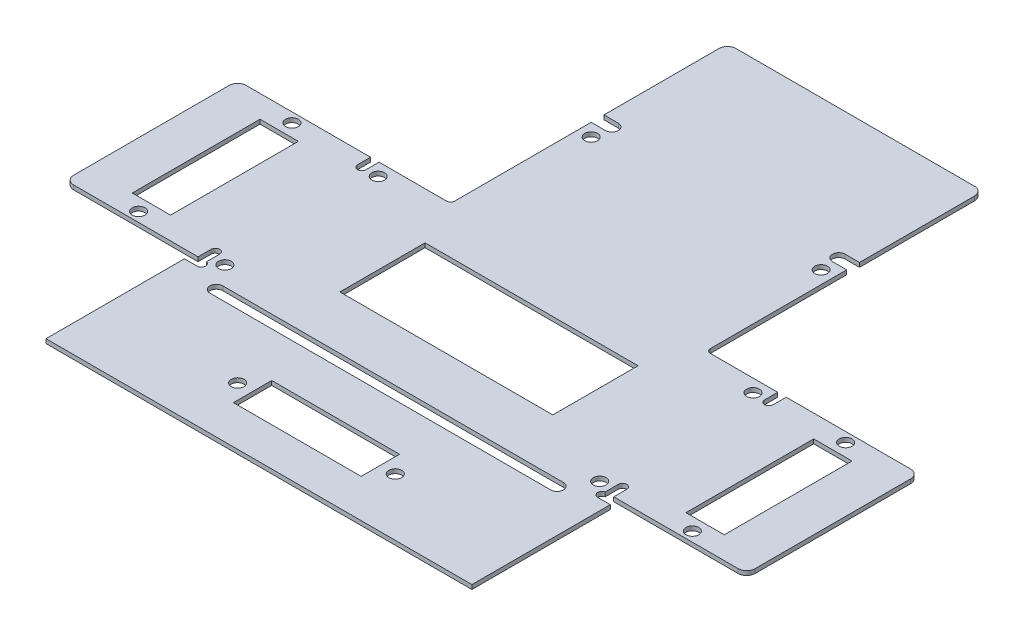
SolidWorks part; units mm, degrees
ref_plane "Front Plane" through (0, 0, 0) normal (0, 0, 1) x (1, 0, 0)
ref_plane "Top Plane" through (0, 0, 0) normal (0, 1, 0) x (1, 0, 0)
ref_plane "Right Plane" through (0, 0, 0) normal (1, 0, 0) x (0, 0, -1)
sketch "Sketch1" plane through (0, 0, 0) normal (0, 1, 0) x (1, 0, 0)
  line L0 (10, 20) -> (90, 20) construction
  line L1 (1, 0) -> (99, 0)
  line L2 (0, 1) -> (0, 99)
  line L3 (1, 100) -> (99, 100)
  line L4 (100, 1) -> (100, 99)
  line L5 (10, 21.5) -> (90, 21.5)
  line L6 (10, 18.5) -> (90, 18.5)
  arc A0 (10, 21.5) -> (10, 18.5) centre (10, 20) ccw
  arc A1 (90, 18.5) -> (90, 21.5) centre (90, 20) ccw
  arc A2 (1, 0) -> (0, 1) centre (1, 1) cw
  arc A3 (99, 0) -> (100, 1) centre (99, 1) ccw
  arc A4 (99, 100) -> (100, 99) centre (99, 99) cw
  arc A5 (0, 99) -> (1, 100) centre (1, 99) cw
  point P7 (50, 20)
  point P14 (0, 0)
  point P17 (100, 0)
  point P20 (100, 100)
  dimension "D7" = 1
  dimension "D1" = 100
  dimension "D2" = 100
  dimension "D3" = 10
  dimension "D4" = 10
  dimension "D5" = 20
  dimension "D6" = 1.5
extrude "Boss-Extrude1" add sketch "Sketch1" along normal blind 1
sketch "Sketch2" plane through (0, 1, 0) normal (0, 1, 0) x (1, 0, 0)
  line L0 (0, 99) -> (0, 1) construction
  line L1 (0, 65) -> (19, 65)
  line L2 (0, 65) -> (0, 100)
  line L3 (0, 100) -> (19, 100)
  line L4 (20, 66) -> (20, 99)
  line L5 (99, 100) -> (1, 100) construction
  line L6 (90, 21.5) -> (10, 21.5) construction
  line L7 (50, 21.5) -> (50, 100) construction
  line L8 (20, 82.5) -> (50, 82.5) construction
  line L9 (100, 100) -> (81, 100)
  line L10 (80, 66) -> (80, 99)
  line L11 (100, 65) -> (81, 65)
  line L12 (100, 65) -> (100, 100)
  line L19 (80, 99) -> (81, 99)
  line L20 (80, 99) -> (80, 100)
  line L21 (80, 100) -> (81, 100)
  line L22 (81, 99) -> (81, 100)
  line L23 (19, 99) -> (20, 99)
  line L24 (19, 99) -> (19, 100)
  line L25 (19, 100) -> (20, 100)
  line L26 (20, 99) -> (20, 100)
  arc A2 (19, 65) -> (20, 66) centre (19, 66) ccw
  arc A3 (19, 100) -> (20, 99) centre (19, 99) cw
  arc A6 (81, 100) -> (80, 99) centre (81, 99) ccw
  arc A7 (81, 65) -> (80, 66) centre (81, 66) cw
  point P20 (20, 65)
  point P23 (20, 100)
  dimension "D7" = 1
  dimension "D1" = 20
  dimension "D2" = 0
  dimension "D3" = 35
extrude "Cut-Extrude2" cut sketch "Sketch2" against normal blind 1
sketch "Sketch3" plane through (0, 1, 0) normal (0, 1, 0) x (1, 0, 0)
  line L0 (0, 65) -> (0, 1) construction
  line L1 (100, 1) -> (100, 65) construction
  line L2 (80, 66) -> (80, 100) construction
  line L3 (90, 21.5) -> (10, 21.5) construction
  line L4 (80, 100) -> (20, 100) construction
  line L5 (20, 66) -> (20, 100) construction
  line L6 (0, 65) -> (19, 65) construction
  line L7 (100, 65) -> (81, 65) construction
  circle A0 centre (6, 26) radius 1.5
  circle A1 centre (23, 95) radius 1.5
  circle A2 centre (77, 95) radius 1.5
  circle A3 centre (94, 26) radius 1.5
  circle A4 centre (6, 62) radius 1.5
  circle A5 centre (94, 62) radius 1.5
  dimension "D2" = 3
  dimension "D10" = 3
  dimension "D1" = 6
  dimension "D3" = 6
  dimension "D4" = 3
  dimension "D5" = 4.5
  dimension "D6" = 4.5
  dimension "D7" = 5
  dimension "D8" = 5
  dimension "D9" = 3
  dimension "D11" = 3
  dimension "D12" = 3
  dimension "D13" = 6
  dimension "D14" = 6
extrude "Cut-Extrude3" cut sketch "Sketch3" against normal blind 1
sketch "Sketch4" plane through (0, 1, 0) normal (0, 1, 0) x (1, 0, 0)
  line L0 (100, 1) -> (100, 65) construction
  line L1 (0, 0) -> (100, 0)
  line L2 (0, 0) -> (0, -10)
  line L3 (0, -10) -> (100, -10)
  line L4 (100, 0) -> (100, -10)
  line L6 (0, 1) -> (1, 1)
  line L7 (0, 1) -> (0, 0)
  line L8 (0, 0) -> (1, 0)
  line L9 (1, 1) -> (1, 0)
  line L10 (100, 0) -> (98.6014, 0)
  line L11 (100, 0) -> (100, 1.3459)
  line L12 (100, 1.3459) -> (98.6014, 1.3459)
  line L13 (98.6014, 0) -> (98.6014, 1.3459)
  arc M23 (0, 1) -> (1, 0) centre (1, 1) ccw
  line M24 (1, 0) -> (99, 0)
  arc M25 (99, 0) -> (100, 1) centre (99, 1) ccw
  line M26 (100, 1) -> (100, 65)
  dimension "D1" = 0
  dimension "D2" = 10
extrude "Boss-Extrude2" add sketch "Sketch4" against normal blind 1 contours L4 L1 L2 L3 M24 | L13 L1 L12 M25 M26 | L1 L11 M25 | L7 L1 M23 | L9 L6 M23
sketch "Sketch5" plane through (0, 1, 0) normal (0, 1, 0) x (1, 0, 0)
  line L0 (90, 21.5) -> (10, 21.5) construction
  line L1 (100, 65) -> (128, 65)
  line L2 (100, 65) -> (100, 24.5)
  line L3 (100, 24.5) -> (128, 24.5)
  line L4 (130, 63) -> (130, 26.5)
  line L5 (50, 21.5) -> (50, 100) construction
  line L6 (80, 100) -> (20, 100) construction
  line L7 (0, 24.5) -> (-28, 24.5)
  line L8 (-30, 63) -> (-30, 26.5)
  line L9 (0, 65) -> (-28, 65)
  line L10 (0, 65) -> (0, 24.5)
  line L12 (80, 100) -> (20, 100)
  line L13 (80, 100) -> (80, 128)
  line L14 (78, 130) -> (22, 130)
  line L15 (20, 100) -> (20, 128)
  arc A0 (-30, 63) -> (-28, 65) centre (-28, 63) cw
  arc A1 (-28, 24.5) -> (-30, 26.5) centre (-28, 26.5) cw
  arc A2 (128, 24.5) -> (130, 26.5) centre (128, 26.5) ccw
  arc A3 (128, 65) -> (130, 63) centre (128, 63) cw
  arc A4 (80, 128) -> (78, 130) centre (78, 128) ccw
  arc A5 (22, 130) -> (20, 128) centre (22, 128) ccw
  point P22 (-30, 65)
  point P25 (-30, 24.5)
  point P28 (130, 24.5)
  point P31 (130, 65)
  point P36 (20, 130)
  dimension "D4" = 2
  dimension "D1" = 30
  dimension "D2" = 3
  dimension "D3" = 30
extrude "Boss-Extrude3" add sketch "Sketch5" against normal blind 1
sketch "Sketch6" plane through (0, 1, 0) normal (0, 1, 0) x (1, 0, 0)
  line L0 (119.5, 29.75) -> (110.5, 29.75)
  line L1 (50, 21.5) -> (50, 130) construction
  line L2 (90, 21.5) -> (10, 21.5) construction
  line L3 (78, 130) -> (22, 130) construction
  line L4 (-30, 44.75) -> (50, 44.75) construction
  line L5 (-30, 63) -> (-30, 26.5) construction
  line L6 (10, 18.5) -> (90, 18.5) construction
  line L7 (-19.5, 59.75) -> (-10.5, 59.75)
  line L8 (65, -1) -> (35, -1)
  line L9 (65, -1) -> (65, 8)
  line L10 (65, 8) -> (35, 8)
  line L11 (35, -1) -> (35, 8)
  line L12 (-19.5, 59.75) -> (-19.5, 29.75)
  line L13 (-19.5, 29.75) -> (-10.5, 29.75)
  line L14 (-10.5, 59.75) -> (-10.5, 29.75)
  line L15 (110.5, 59.75) -> (110.5, 29.75)
  line L16 (119.5, 59.75) -> (110.5, 59.75)
  line L17 (119.5, 59.75) -> (119.5, 29.75)
  circle A0 centre (31.5, 3.5) radius 1.5
  circle A1 centre (-15, 62.75) radius 1.5
  circle A2 centre (-15, 26.75) radius 1.5
  circle A3 centre (68.5, 3.5) radius 1.5
  circle A4 centre (115, 26.75) radius 1.5
  circle A5 centre (115, 62.75) radius 1.5
  dimension "D3" = 3
  dimension "D4" = 3
  dimension "D1" = 18.5
  dimension "D2" = 18
  dimension "D5" = 15
  dimension "D6" = 15
  dimension "D7" = 30
  dimension "D8" = 9
  dimension "D9" = 4.5
  dimension "D10" = 4.5
  dimension "D11" = 30
  dimension "D12" = 9
  dimension "D13" = 15
  dimension "D14" = 15
extrude "Cut-Extrude4" cut sketch "Sketch6" against normal blind 1
sketch "Sketch7" plane through (0, 1, 0) normal (0, 1, 0) x (1, 0, 0)
  line L0 (0, 23.5) -> (2.9727, 23.5) construction
  line L1 (0, 24.5) -> (0, -10) construction
  line L2 (0, 24.5) -> (2.9727, 24.5)
  line L3 (0, 22.5) -> (2.9727, 22.5)
  line L4 (-28, 24.5) -> (0, 24.5) construction
  line L5 (50, 21.5) -> (50, 130) construction
  line L8 (19.9964, 99.5) -> (23.3592, 99.5) construction
  line L9 (19.9964, 101) -> (23.3592, 101)
  line L10 (19.9964, 98) -> (23.3592, 98)
  line L11 (90, 21.5) -> (10, 21.5) construction
  line L12 (78, 130) -> (22, 130) construction
  line L13 (2.2, 24.5) -> (2.2, 27.5568) construction
  line L14 (1.2, 24.5) -> (1.2, 27.5568)
  line L15 (3.2, 24.5) -> (3.2, 27.5568)
  line L16 (-30, 44.75) -> (-19.5, 44.75) construction
  line L17 (-30, 63) -> (-30, 26.5) construction
  line L18 (-19.5, 59.75) -> (-19.5, 29.75) construction
  line L19 (2.2, 65) -> (2.2, 61.9432) construction
  line L20 (1.2, 65) -> (1.2, 61.9432)
  line L21 (3.2, 65) -> (3.2, 61.9432)
  line L22 (80.0036, 99.5) -> (76.6408, 99.5) construction
  line L23 (80.0036, 101) -> (76.6408, 101)
  line L24 (80.0036, 98) -> (76.6408, 98)
  line L25 (97.8, 24.5) -> (97.8, 27.5568) construction
  line L26 (98.8, 24.5) -> (98.8, 27.5568)
  line L27 (96.8, 24.5) -> (96.8, 27.5568)
  line L28 (100, 23.5) -> (97.0273, 23.5) construction
  line L29 (100, 24.5) -> (97.0273, 24.5)
  line L30 (100, 22.5) -> (97.0273, 22.5)
  line L31 (97.8, 65) -> (97.8, 61.9432) construction
  line L32 (98.8, 65) -> (98.8, 61.9432)
  line L33 (96.8, 65) -> (96.8, 61.9432)
  arc A0 (0, 24.5) -> (0, 22.5) centre (0, 23.5) ccw
  arc A1 (2.9727, 22.5) -> (2.9727, 24.5) centre (2.9727, 23.5) ccw
  arc A4 (19.9964, 101) -> (19.9964, 98) centre (19.9964, 99.5) ccw
  arc A5 (23.3592, 98) -> (23.3592, 101) centre (23.3592, 99.5) ccw
  circle A6 centre (23, 95) radius 1.5 construction
  arc A7 (1.2, 24.5) -> (3.2, 24.5) centre (2.2, 24.5) ccw
  arc A8 (3.2, 27.5568) -> (1.2, 27.5568) centre (2.2, 27.5568) ccw
  arc A9 (1.2, 65) -> (3.2, 65) centre (2.2, 65) cw
  arc A10 (3.2, 61.9432) -> (1.2, 61.9432) centre (2.2, 61.9432) cw
  arc A11 (80.0036, 101) -> (80.0036, 98) centre (80.0036, 99.5) cw
  arc A12 (76.6408, 98) -> (76.6408, 101) centre (76.6408, 99.5) cw
  arc A13 (98.8, 24.5) -> (96.8, 24.5) centre (97.8, 24.5) cw
  arc A14 (96.8, 27.5568) -> (98.8, 27.5568) centre (97.8, 27.5568) cw
  arc A15 (100, 24.5) -> (100, 22.5) centre (100, 23.5) cw
  arc A16 (97.0273, 22.5) -> (97.0273, 24.5) centre (97.0273, 23.5) cw
  arc A17 (98.8, 65) -> (96.8, 65) centre (97.8, 65) ccw
  arc A18 (96.8, 61.9432) -> (98.8, 61.9432) centre (97.8, 61.9432) ccw
  point P4 (1.4864, 23.5)
  point P20 (21.6778, 99.5)
  point P28 (2.2, 26.0284)
  point P41 (2.2, 63.4716)
  point P48 (78.3222, 99.5)
  point P55 (97.8, 26.0284)
  point P62 (98.5136, 23.5)
  point P69 (97.8, 63.4716)
  point P74 (2.9727, 23.5)
  line M44 (19, 65) -> (-28, 65)
  line M49 (0, 24.5) -> (0, -10)
  line M51 (100, -10) -> (100, 24.5)
  line M56 (128, 65) -> (81, 65)
  line M58 (80, 66) -> (80, 128)
  line M62 (20, 128) -> (20, 66)
  dimension "D1" = 1
  dimension "D2" = 1
  dimension "D3" = 4.5
  dimension "D4" = 2.2
  dimension "D5" = 1
extrude "Cut-Extrude5" cut sketch "Sketch7" against normal blind 1 contours A10 L21 L20 M44 | A7 L2 L3 A1 M49 | L15 A8 L14 L2 | L2 A7 | A16 L30 L29 A13 M51 | A14 L27 L29 L26 | A13 L29 | L33 A18 L32 M56 | A12 L24 L23 M58 | L10 A5 L9 M62
sketch "Sketch8" plane through (0, 1, 0) normal (0, 1, 0) x (1, 0, 0)
  line L0 (20, 66) -> (20, 98) construction
  line L1 (25, 54) -> (75, 54)
  line L2 (25, 54) -> (25, 34)
  line L3 (25, 34) -> (75, 34)
  line L4 (75, 54) -> (75, 34)
  line L5 (80, 66) -> (80, 98) construction
  line L6 (90, 21.5) -> (10, 21.5) construction
  point P4 (25, 44)
  dimension "D1" = 5
  dimension "D2" = 5
  dimension "D3" = 12.5
  dimension "D4" = 20
extrude "Cut-Extrude6" cut sketch "Sketch8" against normal blind 1
